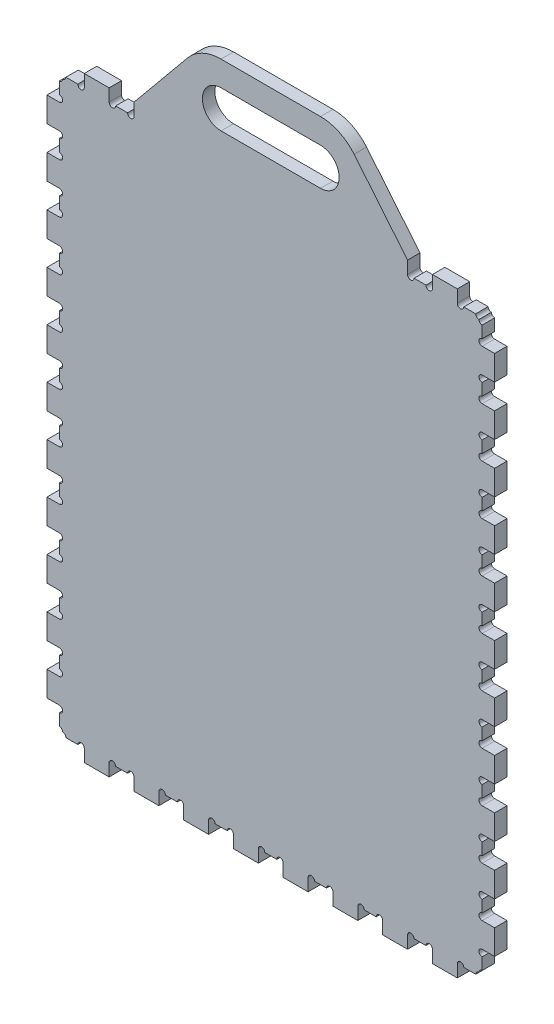
SolidWorks part; units mm, degrees
ref_plane "Front Plane" through (0, 0, 0) normal (0, 0, 1) x (1, 0, 0)
ref_plane "Top Plane" through (0, 0, 0) normal (0, 1, 0) x (1, 0, 0)
ref_plane "Right Plane" through (0, 0, 0) normal (1, 0, 0) x (0, 0, -1)
sketch "Sketch1" plane through (0, 0, 0) normal (0, 0, 1) x (1, 0, 0)
  line L1 (228.6, -304.8) -> (-228.6, -304.8)
  line L2 (228.6, -304.8) -> (228.6, 304.8)
  line L3 (228.6, 304.8) -> (-228.6, 304.8)
  line L4 (-228.6, -304.8) -> (-228.6, 304.8)
  line L5 (228.6, -304.8) -> (-228.6, 304.8) construction
  line L6 (228.6, 304.8) -> (-228.6, -304.8) construction
  line L9 (-203.2, 304.8) -> (-228.6, 304.8) construction
  point P0 (0, 0)
  dimension "D1" = 457.2
  dimension "D2" = 609.6
extrude "Boss-Extrude1" add sketch "Sketch1" along normal blind 12.7
sketch "Sketch2" plane through (0, 0, 12.7) normal (0, 0, 1) x (1, 0, 0)
  line L0 (228.6, 304.8) -> (-228.6, 304.8) construction
  line L1 (-215.9, 292.1) -> (-228.6, 292.1) construction
  line L2 (-215.9, 304.8) -> (-190.5, 304.8)
  line L3 (-215.9, 304.8) -> (-215.9, 292.1)
  line L4 (-215.9, 292.1) -> (-190.5, 292.1)
  line L5 (-190.5, 304.8) -> (-190.5, 292.1)
  line L6 (-228.6, 304.8) -> (-228.6, -304.8) construction
  circle A0 centre (-212.598, 292.1) radius 3.302
  circle A1 centre (-193.802, 292.1) radius 3.302
  line M10 (228.6, 304.8) -> (-228.6, 304.8)
  dimension "D4" = 6.604
  dimension "D5" = 6.604
  dimension "D1" = 25.4
  dimension "D2" = 12.7
  dimension "D3" = 12.7
extrude "Cut-Extrude1" cut sketch "Sketch2" against normal through all contours A1 L5 L3 A0 L4 M10 | L4 A0 | L4 A0 | L4 A1 | L4 A1
pattern_linear "LPattern1" count 9 spacing 50.8 along (1, 0, 0) of "Cut-Extrude1"
sketch "Sketch6" plane through (0, 0, 12.7) normal (0, 0, 1) x (1, 0, 0)
  line L1 (-228.6, 304.8) -> (-215.9, 304.8)
  line L2 (-228.6, 304.8) -> (-228.6, 292.1)
  line L3 (-228.6, 292.1) -> (-215.9, 292.1)
  line L4 (-215.9, 304.8) -> (-215.9, 292.1)
extrude "Cut-Extrude4" cut sketch "Sketch6" against normal through all
sketch "Sketch3" plane through (0, 0, 12.7) normal (0, 0, 1) x (1, 0, 0)
  line L0 (-228.6, 292.1) -> (-228.6, -304.8) construction
  line L1 (-228.6, 292.1) -> (-215.9, 292.1)
  line L2 (-228.6, 292.1) -> (-228.6, 266.7)
  line L3 (-228.6, 266.7) -> (-215.9, 266.7)
  line L4 (-215.9, 292.1) -> (-215.9, 266.7)
  line L5 (-215.9, 292.1) -> (-182.9158, 292.1) construction
  line L6 (-182.9158, 292.1) -> (-182.9158, 304.8) construction
  line L8 (-165.1, 304.8) -> (-190.5, 304.8) construction
  circle A0 centre (-215.9, 288.798) radius 3.302
  circle A1 centre (-215.9, 270.002) radius 3.302
  dimension "D3" = 6.604
  dimension "D4" = 6.604
  dimension "D1" = 25.4
  dimension "D2" = 12.7
  dimension "D5" = 12.7
extrude "Cut-Extrude2" cut sketch "Sketch3" against normal through all contours A1 L4 A0 L1 L2 L3 | L4 A0 | L4 A0 | L4 A1 | L4 A1
pattern_linear "LPattern2" count 12 spacing 50.8 along (0, -1, 0) of "Cut-Extrude2"
ref_plane "Plane1" through (0, 0, 0) normal (1, 0, 0) x (0, 0, -1)
ref_plane "Plane2" through (0, 0, 0) normal (0, 1, 0) x (1, 0, 0)
mirror "Mirror6" about plane through (0, 0, 0) normal (1, 0, 0) of "Cut-Extrude4"
mirror "Mirror7" about plane through (0, 0, 0) normal (0, 1, 0) of "Mirror6", "Cut-Extrude4"
mirror "Mirror1" about plane through (0, 0, 0) normal (1, 0, 0) of "LPattern2", "Cut-Extrude2"
mirror "Mirror2" about plane through (0, 0, 0) normal (0, 1, 0) of "LPattern1", "Cut-Extrude1"
sketch "Sketch9" plane through (0, 0, 12.7) normal (0, 0, 1) x (1, 0, 0)
  line L0 (-50.8, 342.9) -> (50.8, 342.9) construction
  line L1 (-50.8, 361.95) -> (50.8, 361.95)
  line L2 (-50.8, 323.85) -> (50.8, 323.85)
  line L3 (0, 342.9) -> (0, 292.1) construction
  line L4 (-6.096, 292.1) -> (6.096, 292.1) construction
  line L5 (-50.8, 387.35) -> (50.8, 387.35)
  line L7 (85.1274, 371.1389) -> (139.7, 304.8)
  line L8 (139.7, 304.8) -> (-139.7, 304.8)
  line L9 (-139.7, 304.8) -> (-85.1274, 371.1389)
  arc A0 (-50.8, 361.95) -> (-50.8, 323.85) centre (-50.8, 342.9) ccw
  arc A1 (50.8, 323.85) -> (50.8, 361.95) centre (50.8, 342.9) ccw
  arc A2 (-50.8, 387.35) -> (-85.1274, 371.1389) centre (-50.8, 342.9) ccw
  arc A3 (85.1274, 371.1389) -> (50.8, 387.35) centre (50.8, 342.9) ccw
  point P2 (0, 342.9)
  dimension "D1" = 38.1
  dimension "D2" = 101.6
  dimension "D3" = 38.1
  dimension "D4" = 25.4
extrude "Boss-Extrude3" add sketch "Sketch9" against normal blind 12.7
sketch "Sketch10" plane through (0, 0, 12.7) normal (0, 0, 1) x (1, 0, 0)
  line L0 (-114.3, 304.8) -> (-114.3, 292.1) construction
  line L1 (-114.3, 304.8) -> (-88.9, 304.8) construction
  line L2 (-88.9, 304.8) -> (-88.9, 292.1) construction
  circle A0 centre (-110.998, 304.8) radius 3.302
  circle A1 centre (-92.202, 304.8) radius 3.302
  dimension "D1" = 6.604
  dimension "D2" = 6.604
extrude "Cut-Extrude6" cut sketch "Sketch10" against normal blind 12.7
pattern_linear "LPattern3" count 5 spacing 50.8 along (1, 0, 0) of "Cut-Extrude6"
sketch "Sketch11" plane through (0, 0, 12.7) normal (0, 0, 1) x (1, 0, 0)
  line L0 (-114.3, 241.3) -> (-215.9, 241.3) construction
  line L1 (-114.3, 241.3) -> (-101.6, 241.3)
  line L2 (-114.3, 241.3) -> (-114.3, 215.9)
  line L3 (-114.3, 215.9) -> (-101.6, 215.9)
  line L4 (-101.6, 241.3) -> (-101.6, 215.9)
  circle A0 centre (-114.3, 237.998) radius 3.302
  circle A1 centre (-101.6, 237.998) radius 3.302
  circle A2 centre (-101.6, 219.202) radius 3.302
  circle A3 centre (-114.3, 219.202) radius 3.302
  arc A4 (-215.9, 234.696) -> (-215.9, 241.3) centre (-215.9, 237.998) ccw construction
  dimension "D3" = 6.604
  dimension "D1" = 12.7
  dimension "D2" = 25.4
  dimension "D4" = 101.6
extrude "Cut-Extrude7" cut sketch "Sketch11" against normal through all contours A3 L3 A2 L4 A1 L1 A0 L2 | L2 A0 | L2 A3 | L2 A3 | L4 A2 | L4 A2 | L4 A1 | L4 A1
pattern_linear "LPattern4" count 10 spacing 50.8 along (0, -1, 0) of "Cut-Extrude7"
sketch "Sketch12" plane through (0, 0, 12.7) normal (0, 0, 1) x (1, 0, 0)
  line L1 (-119.1237, 314.3954) -> (119.9637, 314.3954)
  line L2 (-119.1237, 314.3954) -> (-119.1237, 276.177)
  line L3 (-119.1237, 276.177) -> (119.9637, 276.177)
  line L4 (119.9637, 314.3954) -> (119.9637, 276.177)
extrude "Boss-Extrude4" add sketch "Sketch12" against normal blind 12.7
sketch "Sketch13" plane through (0, 0, 0) normal (0, 0, 1) x (1, 0, 0)
  line L0 (-215.9, -266.7) -> (-139.7, -266.7) construction
  line L2 (-139.7, 316.0285) -> (-139.7, -266.7)
  line L3 (-139.7, -266.7) -> (-126.492, -266.7)
  line L4 (-126.492, 333.1058) -> (-126.492, -266.7)
  line L5 (-139.7, 316.0285) -> (-126.492, 333.1058)
  line L6 (-139.7, -292.1) -> (-139.7, -266.7)
  arc A0 (-139.7, -292.1) -> (-146.304, -292.1) centre (-143.002, -292.1) ccw construction
  circle A1 centre (-136.398, -266.7) radius 3.302
  circle A2 centre (-129.794, -266.7) radius 3.302
  dimension "D3" = 6.604
  dimension "D1" = 13.208
  dimension "D2" = 25.4
extrude "Cut-Extrude12" cut sketch "Sketch13" along normal blind 6.35 contours A2 L4 L5 L2 A1 L3 | L3 A1 | L3 A1 | L3 A2 | L3 A2
sketch "Sketch14" plane through (0, 0, 12.7) normal (0, 0, 1) x (1, 0, 0)
  line L1 (-86.6076, 260.2827) -> (-122.9429, 260.2827)
  line L2 (-86.6076, 260.2827) -> (-86.6076, -258.3673)
  line L3 (-86.6076, -258.3673) -> (-122.9429, -258.3673)
  line L4 (-122.9429, 260.2827) -> (-122.9429, -258.3673)
extrude "Boss-Extrude5" add sketch "Sketch14" against normal blind 12.7
